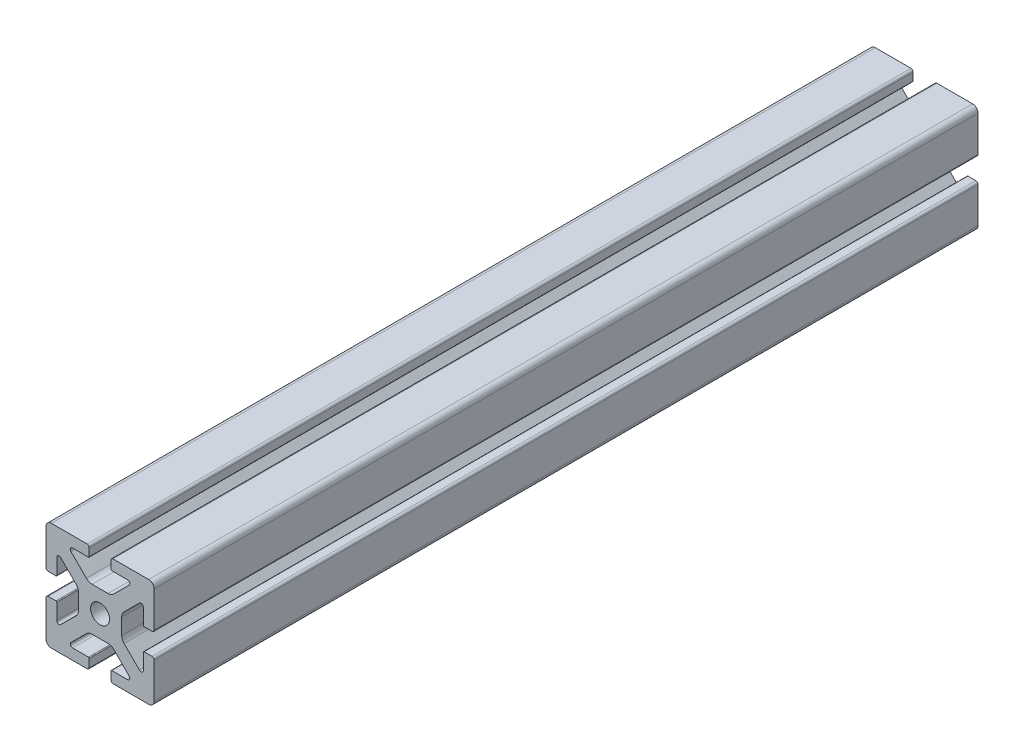
SolidWorks part; units mm, degrees
ref_plane "Front Plane" through (0, 0, 0) normal (0, 0, 1) x (1, 0, 0)
ref_plane "Top Plane" through (0, 0, 0) normal (0, 1, 0) x (1, 0, 0)
ref_plane "Right Plane" through (0, 0, 0) normal (1, 0, 0) x (0, 0, -1)
sketch "Sketch1" plane through (0, 0, 0) normal (0, 0, 1) x (1, 0, 0)
  line L0 (0, 20) -> (0, -20) construction
  line L1 (20, 0) -> (-20, 0) construction
  line L2 (-4, 20) -> (4, 20) construction
  line L3 (-11, 16) -> (11, 16) construction
  circle A0 centre (0, 0) radius 3.5 construction
  point P4 (0, 0)
  point P8 (0, 0)
  point P10 (0, 8)
  point P14 (0, 20)
  point P17 (0, 16)
  dimension "Thru Hole" = 7
  dimension "Height" = 40
  dimension "T Slot Depth" = 12
  dimension "T Slot Top Width" = 8
  dimension "T Slot Max Width" = 22
  dimension "Wall" = 4
sketch "Sketch2" plane through (0, 0, 0) normal (1, 0, 0) x (0, 0, -1)
  line L0 (152.4, 0) -> (-152.4, 0) construction
  point P4 (0, 0)
  dimension "D1" = 304.8
sketch "Sketch3" plane through (0, 0, 0) normal (0, 0, 1) x (1, 0, 0)
  line L0 (4.7874, 20) -> (18, 20)
  line L1 (20, 18) -> (20, -18) construction
  line L2 (18, -20) -> (-18, -20) construction
  line L3 (-20, 20) -> (20, -20) construction
  line L4 (4, 19.2126) -> (4, 16.3048)
  line L5 (-11, 16) -> (11, 16) construction
  line L6 (4.3048, 16) -> (10.1618, 16)
  line L7 (10.7545, 14.5691) -> (5.0641, 8.8787)
  line L8 (2.9428, 8) -> (-2.9428, 8)
  line L9 (0, 20) -> (0, -20) construction
  line L10 (11, 16) -> (11, 0) construction
  line L11 (20, 0) -> (-20, 0) construction
  line L12 (0, 0) -> (0, 20) construction
  line L13 (-4, 19.2126) -> (-4, 16.3048)
  line L14 (-10.7545, 14.5691) -> (-5.0641, 8.8787)
  line L15 (-4.3048, 16) -> (-10.1618, 16)
  line L16 (-4.7874, 20) -> (-18, 20)
  line L17 (0, 0) -> (-20, 0) construction
  line L18 (-20, 4.7874) -> (-20, 18)
  line L19 (-16, 4.3048) -> (-16, 10.1618)
  line L20 (-14.5691, 10.7545) -> (-8.8787, 5.0641)
  line L21 (-19.2126, 4) -> (-16.3048, 4)
  line L22 (-8, -2.9428) -> (-8, 2.9428)
  line L23 (-14.5691, -10.7545) -> (-8.8787, -5.0641)
  line L24 (-16, -4.3048) -> (-16, -10.1618)
  line L25 (-19.2126, -4) -> (-16.3048, -4)
  line L26 (-20, -4.7874) -> (-20, -18)
  line L27 (19.2126, -4) -> (16.3048, -4)
  line L28 (16, -4.3048) -> (16, -10.1618)
  line L29 (14.5691, -10.7545) -> (8.8787, -5.0641)
  line L30 (8, -2.9428) -> (8, 2.9428)
  line L31 (19.2126, 4) -> (16.3048, 4)
  line L32 (14.5691, 10.7545) -> (8.8787, 5.0641)
  line L33 (16, 4.3048) -> (16, 10.1618)
  line L34 (20, 18) -> (20, 4.7874)
  line L35 (20, -4.7874) -> (20, -18)
  line L36 (4.7874, -20) -> (18, -20)
  line L37 (-4.7874, -20) -> (-18, -20)
  line L38 (-14.5691, -10.7545) -> (-8.8787, -5.0641)
  line L39 (-4.3048, -16) -> (-10.1618, -16)
  line L40 (-10.7545, -14.5691) -> (-5.0641, -8.8787)
  line L41 (-4, -19.2126) -> (-4, -16.3048)
  line L42 (2.9428, -8) -> (-2.9428, -8)
  line L43 (10.7545, -14.5691) -> (5.0641, -8.8787)
  line L44 (4.3048, -16) -> (10.1618, -16)
  line L45 (4, -19.2126) -> (4, -16.3048)
  arc A0 (10.1618, 16) -> (10.7545, 14.5691) centre (10.1618, 15.1618) cw
  arc A1 (5.0641, 8.8787) -> (2.9428, 8) centre (2.9428, 11) cw
  circle A2 centre (0, 0) radius 3.5 construction
  circle A3 centre (0, 0) radius 3.5
  arc A4 (4.7874, 20) -> (4, 19.2126) centre (4.7874, 19.2126) ccw
  arc A5 (4, 16.3048) -> (4.3048, 16) centre (4.3048, 16.3048) ccw
  arc A6 (-4.7874, 20) -> (-4, 19.2126) centre (-4.7874, 19.2126) cw
  arc A7 (-10.1618, 16) -> (-10.7545, 14.5691) centre (-10.1618, 15.1618) ccw
  arc A8 (-5.0641, 8.8787) -> (-2.9428, 8) centre (-2.9428, 11) ccw
  arc A9 (-4, 16.3048) -> (-4.3048, 16) centre (-4.3048, 16.3048) cw
  arc A10 (-16.3048, 4) -> (-16, 4.3048) centre (-16.3048, 4.3048) ccw
  arc A11 (-8.8787, 5.0641) -> (-8, 2.9428) centre (-11, 2.9428) cw
  arc A12 (-16, 10.1618) -> (-14.5691, 10.7545) centre (-15.1618, 10.1618) cw
  arc A13 (-20, 4.7874) -> (-19.2126, 4) centre (-19.2126, 4.7874) ccw
  arc A14 (-16.3048, -4) -> (-16, -4.3048) centre (-16.3048, -4.3048) cw
  arc A15 (-20, -4.7874) -> (-19.2126, -4) centre (-19.2126, -4.7874) cw
  arc A16 (-8.8787, -5.0641) -> (-8, -2.9428) centre (-11, -2.9428) ccw
  arc A17 (-16, -10.1618) -> (-14.5691, -10.7545) centre (-15.1618, -10.1618) ccw
  arc A26 (-18, -20) -> (-20, -18) centre (-18, -18) cw
  arc A27 (-18, 20) -> (-20, 18) centre (-18, 18) ccw
  arc A28 (18, 20) -> (20, 18) centre (18, 18) cw
  arc A29 (20, -18) -> (18, -20) centre (18, -18) cw
  arc A30 (16, -10.1618) -> (14.5691, -10.7545) centre (15.1618, -10.1618) cw
  arc A31 (8.8787, -5.0641) -> (8, -2.9428) centre (11, -2.9428) cw
  arc A32 (20, -4.7874) -> (19.2126, -4) centre (19.2126, -4.7874) ccw
  arc A33 (16.3048, -4) -> (16, -4.3048) centre (16.3048, -4.3048) ccw
  arc A34 (20, 4.7874) -> (19.2126, 4) centre (19.2126, 4.7874) cw
  arc A35 (16, 10.1618) -> (14.5691, 10.7545) centre (15.1618, 10.1618) ccw
  arc A36 (8.8787, 5.0641) -> (8, 2.9428) centre (11, 2.9428) ccw
  arc A37 (16.3048, 4) -> (16, 4.3048) centre (16.3048, 4.3048) cw
  arc A38 (-4, -16.3048) -> (-4.3048, -16) centre (-4.3048, -16.3048) ccw
  arc A39 (-5.0641, -8.8787) -> (-2.9428, -8) centre (-2.9428, -11) cw
  arc A40 (-10.1618, -16) -> (-10.7545, -14.5691) centre (-10.1618, -15.1618) cw
  arc A41 (-4.7874, -20) -> (-4, -19.2126) centre (-4.7874, -19.2126) ccw
  arc A42 (4, -16.3048) -> (4.3048, -16) centre (4.3048, -16.3048) cw
  arc A43 (4.7874, -20) -> (4, -19.2126) centre (4.7874, -19.2126) cw
  arc A44 (5.0641, -8.8787) -> (2.9428, -8) centre (2.9428, -11) ccw
  arc A45 (10.1618, -16) -> (10.7545, -14.5691) centre (10.1618, -15.1618) ccw
  point P36 (4, 20)
  point P39 (4, 16)
  point P49 (0, 8)
  point P77 (-8, 0)
  point P78 (-16, -4)
  point P79 (-20, -4)
  point P104 (-20, -20)
  point P110 (20, 20)
  point P114 (20, -4)
  point P115 (16, -4)
  point P116 (8, 0)
  point P141 (0, -8)
  dimension "D1" = 3
  dimension "D2" = 0.8382
  dimension "D4" = 0.7874
  dimension "D5" = 0.3048
  dimension "D6" = 2
  dimension "D3" = 45
extrude "Boss-Extrude1" add sketch "Sketch3" along normal up to vertex (152.4 mm away) and the other way up to vertex (152.4 mm away) contours A45 L44 A42 L45 A43 L36 A29 L35 A32 L27 A33 L28 A30 L29 A31 L30 A36 L32 A35 L33 A37 L31 A34 L34 A28 L0 A4 L4 A5 L6 A0 L7 A1 L8 A8 L14 A7 L15 A9 L13 A6 L16 A27 L18 A13 L21 A10 L19 A12 L20 A11 up to point (0, 0, 152.4) other way up to point (0, 0, -152.4)
